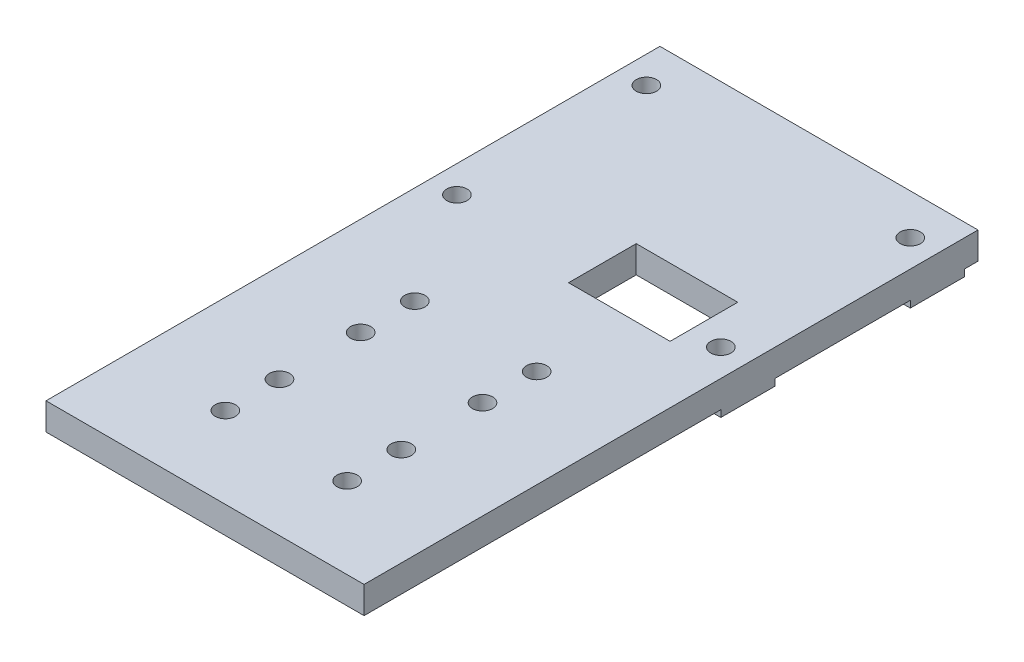
SolidWorks part; units mm, degrees
material "聚脂树脂"
ref_plane "前视基准面" through (0, 0, 0) normal (0, 0, 1) x (1, 0, 0)
ref_plane "上视基准面" through (0, 0, 0) normal (0, 1, 0) x (1, 0, 0)
ref_plane "右视基准面" through (0, 0, 0) normal (1, 0, 0) x (0, 0, -1)
other "Configuration Table"
sketch "草图1" plane through (0, 0, 0) normal (0, 1, 0) x (1, 0, 0)
  line L0 (0, 0) -> (0, 40.9092) construction
  line L1 (-23.5, -20) -> (23.5, -20)
  line L2 (-23.5, -20) -> (-23.5, 20)
  line L3 (-23.5, 20) -> (23.5, 20)
  line L4 (23.5, -20) -> (23.5, 20)
  line L5 (-23.5, -20) -> (23.5, 20) construction
  line L6 (-23.5, 20) -> (23.5, -20) construction
  line L7 (0, 0) -> (66.2179, 0) construction
  line L16 (0, 0) -> (0, -21.1131) construction
  line L17 (-15, -7) -> (15, -7)
  line L18 (15, -7) -> (15, -17)
  line L19 (15, -17) -> (-15, -17)
  line L20 (-15, -7) -> (-15, -17)
  line L21 (-23.5, -20) -> (-23.5, -75.72)
  line L22 (-23.5, -75.72) -> (23.5, -75.72)
  line L23 (23.5, -75.72) -> (23.5, -20)
  line L24 (0, -7) -> (0, -17)
  circle A0 centre (19.5, 14) radius 1.5
  circle A1 centre (19.5, -14) radius 1.5
  circle A2 centre (-19.5, -14) radius 1.5
  circle A3 centre (-19.5, 14) radius 1.5
  point P0 (0, 0)
  point P23 (0, -17)
  point P24 (0, -7)
  dimension "D3" = 3
  dimension "D4" = 39
  dimension "D5" = 28
  dimension "D1" = 47
  dimension "D2" = 40
  dimension "D6" = 30
  dimension "D7" = 10
  dimension "D8" = 7
  dimension "D9" = 75.72
extrude "凸台-拉伸1" add sketch "草图1" along normal blind 4 contours L1 L4 L3 L2 A1 A0 L20 L17 L18 L19 A2 A3 | L22 L23 L1 L21 | L24 L17 L20 L19
sketch "草图3" plane through (0, 0, 0) normal (0, -1, 0) x (1, 0, 0)
  line L0 (0, 0) -> (41.6004, 0) construction
  line L5 (15.5, -18) -> (23.5, -18)
  line L6 (15.5, 10) -> (23.5, 10)
  line L7 (0, 0) -> (0, 32.2448) construction
  line L16 (15.5, 10) -> (15.5, 18)
  line L17 (15.5, 18) -> (23.5, 18)
  line L22 (23.5, 10) -> (23.5, 18)
  line L23 (15.5, 10) -> (23.5, 18) construction
  line L24 (15.5, 18) -> (23.5, 10) construction
  line L25 (23.5, -10) -> (23.5, -18)
  line L26 (15.5, -10) -> (23.5, -10)
  line L27 (15.5, -10) -> (15.5, -18)
  line L28 (-15.5, -10) -> (-15.5, -18)
  line L29 (-15.5, -10) -> (-23.5, -10)
  line L30 (-23.5, -10) -> (-23.5, -18)
  line L31 (-15.5, -18) -> (-23.5, -18)
  line L32 (-15.5, 18) -> (-23.5, 18)
  line L33 (-23.5, 10) -> (-23.5, 18)
  line L34 (-15.5, 10) -> (-23.5, 10)
  line L35 (-15.5, 10) -> (-15.5, 18)
  circle A8 centre (-19.5, 14) radius 1.5 construction
  circle A9 centre (-19.5, -14) radius 1.5 construction
  circle A10 centre (19.5, -14) radius 1.5 construction
  circle A11 centre (19.5, 14) radius 1.5 construction
  circle A12 centre (-19.5, 14) radius 1.5
  circle A13 centre (-19.5, -14) radius 1.5
  circle A14 centre (19.5, -14) radius 1.5
  circle A15 centre (19.5, 14) radius 1.5
  point P0 (19.5, 14)
  point P22 (-19.5, 14)
  dimension "D1" = 8
  dimension "D2" = 8
extrude "凸台-拉伸2" add sketch "草图3" along normal blind 1
sketch "草图4" plane through (0, 4, 0) normal (0, 1, 0) x (1, 0, 0)
  line L0 (0, 0) -> (0, -70.72) construction
  line L1 (-23.5, -75.72) -> (23.5, -75.72) construction
  line L2 (-23.5, -70.72) -> (23.5, -70.72)
  line L3 (-23.5, -75.72) -> (-23.5, 20) construction
  line L4 (23.5, -75.72) -> (23.5, 20) construction
  line L5 (23.5, -70.72) -> (23.5, -75.72)
  line L6 (23.5, -75.72) -> (-23.5, -75.72)
  line L7 (-23.5, -75.72) -> (-23.5, -70.72)
  circle A0 centre (9, -30.72) radius 1.5
  circle A1 centre (9, -50.72) radius 1.5
  circle A2 centre (-9, -50.72) radius 1.5
  circle A3 centre (-9, -30.72) radius 1.5
  circle A4 centre (-9, -38.72) radius 1.5
  circle A5 centre (9, -38.72) radius 1.5
  circle A6 centre (9, -58.72) radius 1.5
  circle A7 centre (-9, -58.72) radius 1.5
  dimension "D1" = 3
  dimension "D2" = 3
  dimension "D3" = 20
  dimension "D4" = 18
  dimension "D5" = 25
  dimension "D6" = 18
  dimension "D9" = 8
  dimension "D7" = 5
  dimension "D8" = 2
extrude "切除-拉伸2" cut sketch "草图4" against normal blind 4
sketch "草图5" plane through (0, 4, 0) normal (0, 1, 0) x (1, 0, 0)
  line L0 (0, -5) -> (0, 34.0121) construction
  line L1 (0, -5) -> (39.4094, -5) construction
  line L2 (15, -5) -> (23.5, -5)
  line L3 (23.5, -70.72) -> (23.5, 20) construction
  line L4 (23.5, -5) -> (23.5, -9)
  line L5 (23.5, -9) -> (15, -9)
  line L6 (15, -9) -> (15, -5)
  line L7 (-23.5, -9) -> (-15, -9)
  line L8 (-23.5, -5) -> (-23.5, -9)
  line L9 (-15, -5) -> (-23.5, -5)
  line L10 (-15, -9) -> (-15, -5)
  line L11 (0, 0) -> (38.2779, 0) construction
  line L12 (0, 0) -> (0, 10.5962) construction
  dimension "D1" = 30
  dimension "D2" = 5
  dimension "D3" = 4
